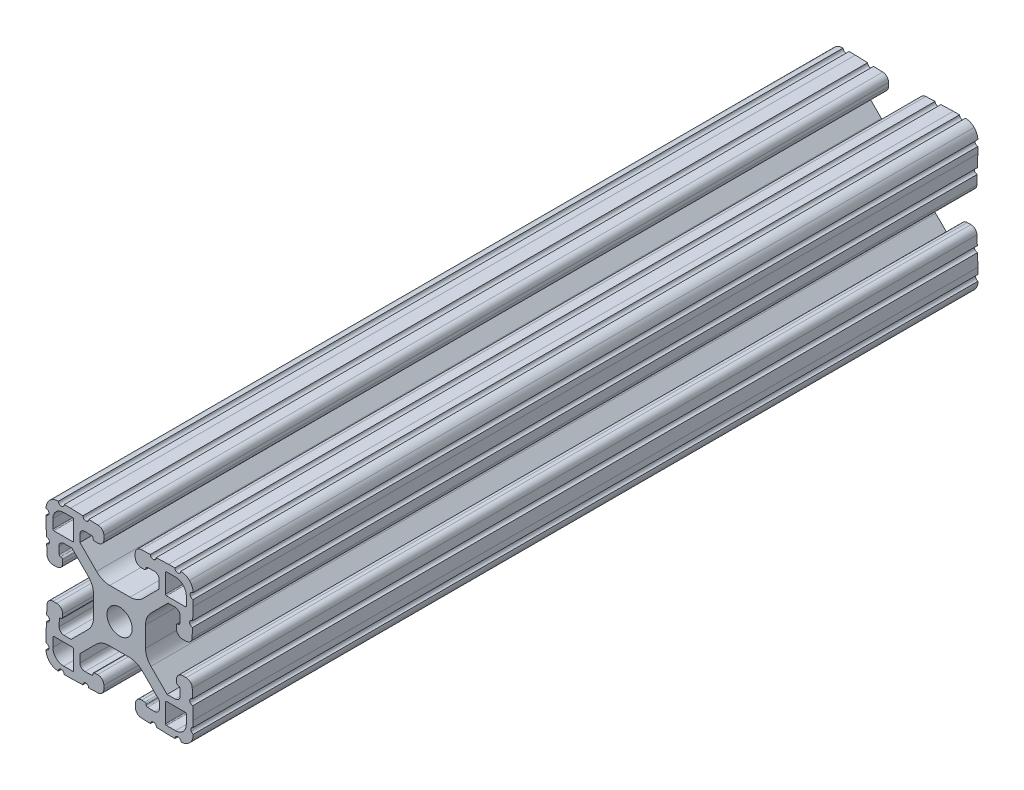
SolidWorks part; units mm, degrees
ref_plane "Front Plane" through (0, 0, 0) normal (0, 0, 1) x (1, 0, 0)
ref_plane "Top Plane" through (0, 0, 0) normal (0, 1, 0) x (1, 0, 0)
ref_plane "Right Plane" through (0, 0, 0) normal (1, 0, 0) x (0, 0, -1)
ref_plane "Plane1" through (0, 0, -25.4) normal (0, 0, -1) x (-1, 0, 0)
sketch "Sketch1" plane through (0, 0, -25.4) normal (0, 0, -1) x (-1, 0, 0)
  line L0 (-83.3577, 88.2941) -> (-83.3577, 93.1709)
  line L1 (-83.1037, 93.4249) -> (-80.767, 93.4249)
  line L2 (-77.9729, 90.6309) -> (-77.9729, 88.2941)
  line L3 (-78.2269, 88.0401) -> (-83.1037, 88.0401)
  line L4 (-83.3577, 59.2291) -> (-83.3577, 64.1059)
  line L5 (-83.1037, 64.3599) -> (-78.2269, 64.3599)
  line L6 (-77.9729, 64.1059) -> (-77.9729, 61.7691)
  line L7 (-80.767, 58.9751) -> (-83.1037, 58.9751)
  line L8 (-107.1423, 93.1709) -> (-107.1423, 88.2941)
  line L9 (-107.3963, 88.0401) -> (-112.2731, 88.0401)
  line L10 (-112.5271, 88.2941) -> (-112.5271, 90.6309)
  line L11 (-109.733, 93.4249) -> (-107.3963, 93.4249)
  line L12 (-107.1423, 64.1059) -> (-107.1423, 59.2291)
  line L13 (-107.3963, 58.9751) -> (-109.733, 58.9751)
  line L14 (-112.5271, 61.7691) -> (-112.5271, 64.1059)
  line L15 (-112.2731, 64.3599) -> (-107.3963, 64.3599)
  line L16 (-88.0437, 91.8626) -> (-86.2967, 91.9236)
  line L17 (-84.9824, 90.6544) -> (-84.9824, 88.8002)
  line L18 (-84.9824, 88.8002) -> (-89.3066, 84.476)
  line L19 (-92.7196, 83.0295) -> (-97.9616, 83.0295)
  line L20 (-101.3202, 84.4207) -> (-105.516, 88.6165)
  line L21 (-105.516, 88.6165) -> (-105.516, 90.7313)
  line L22 (-104.2017, 92.0006) -> (-102.4547, 91.9396)
  line L23 (-101.7262, 91.1059) -> (-100.9297, 91.0781)
  line L24 (-99.2999, 92.6519) -> (-99.2999, 93.5668)
  line L25 (-100.8197, 95.1407) -> (-103.2119, 95.2242)
  line L26 (-104.735, 95.2774) -> (-107.9359, 95.3892)
  line L27 (-107.9359, 95.3892) -> (-109.5615, 95.3892)
  line L28 (-114.2859, 90.6648) -> (-114.2859, 89.0392)
  line L29 (-114.2859, 89.0392) -> (-114.1741, 85.8383)
  line L30 (-114.1209, 84.3152) -> (-114.0374, 81.9231)
  line L31 (-112.4635, 80.4032) -> (-111.5486, 80.4032)
  line L32 (-109.9748, 82.033) -> (-110.0026, 82.8295)
  line L33 (-110.8377, 83.5577) -> (-110.8987, 85.3047)
  line L34 (-109.6294, 86.619) -> (-107.8072, 86.619)
  line L35 (-107.8072, 86.619) -> (-103.3649, 82.1768)
  line L36 (-101.9737, 78.8182) -> (-101.9737, 73.576)
  line L37 (-103.3649, 70.2174) -> (-107.5607, 66.0217)
  line L38 (-107.5607, 66.0217) -> (-109.6524, 66.0217)
  line L39 (-110.9217, 67.336) -> (-110.8607, 69.083)
  line L40 (-110.0322, 69.8124) -> (-110.0043, 70.6089)
  line L41 (-111.5782, 72.2387) -> (-112.4931, 72.2387)
  line L42 (-114.0669, 70.7189) -> (-114.1505, 68.3267)
  line L43 (-114.2036, 66.8036) -> (-114.3154, 63.6027)
  line L44 (-114.3154, 63.6027) -> (-114.3154, 61.9626)
  line L45 (-109.6111, 57.1437) -> (-107.9855, 57.1437)
  line L46 (-107.9855, 57.1437) -> (-104.7846, 57.2555)
  line L47 (-103.2615, 57.3086) -> (-100.8694, 57.3922)
  line L48 (-99.3495, 58.966) -> (-99.3495, 59.8809)
  line L49 (-100.9794, 61.4548) -> (-101.7758, 61.4269)
  line L50 (-102.5054, 60.599) -> (-104.2524, 60.538)
  line L51 (-105.5667, 61.8072) -> (-105.5667, 63.6295)
  line L52 (-105.5667, 63.6295) -> (-101.1311, 68.065)
  line L53 (-97.7725, 69.4562) -> (-92.5304, 69.4562)
  line L54 (-89.1717, 68.065) -> (-84.976, 63.8692)
  line L55 (-84.976, 63.8692) -> (-84.976, 61.7811)
  line L56 (-86.2903, 60.5118) -> (-88.0373, 60.5728)
  line L57 (-88.7596, 61.4332) -> (-89.5561, 61.461)
  line L58 (-91.1859, 59.8872) -> (-91.1859, 58.9723)
  line L59 (-89.6661, 57.3985) -> (-87.2739, 57.3149)
  line L60 (-85.7508, 57.2617) -> (-82.5499, 57.15)
  line L61 (-82.5499, 57.15) -> (-80.9244, 57.15)
  line L62 (-76.2, 61.8744) -> (-76.2, 63.4999)
  line L63 (-76.2, 63.4999) -> (-76.3117, 66.7008)
  line L64 (-76.3649, 68.2239) -> (-76.4484, 70.6161)
  line L65 (-78.0223, 72.1359) -> (-78.9372, 72.1359)
  line L66 (-80.511, 70.5061) -> (-80.4832, 69.7096)
  line L67 (-79.6552, 68.9801) -> (-79.5942, 67.2331)
  line L68 (-80.8634, 65.9188) -> (-82.6857, 65.9188)
  line L69 (-82.6857, 65.9188) -> (-87.1213, 70.3543)
  line L70 (-88.5125, 73.7128) -> (-88.5126, 78.955)
  line L71 (-87.1214, 82.3137) -> (-82.9257, 86.5095)
  line L72 (-82.9257, 86.5095) -> (-80.8375, 86.5095)
  line L73 (-79.5682, 85.1951) -> (-79.6293, 83.4482)
  line L74 (-80.4896, 82.7258) -> (-80.5175, 81.9294)
  line L75 (-78.9436, 80.2995) -> (-78.0287, 80.2995)
  line L76 (-76.4549, 81.8194) -> (-76.3713, 84.2115)
  line L77 (-76.3182, 85.7346) -> (-76.2064, 88.9355)
  line L78 (-76.2064, 88.9355) -> (-76.2064, 90.5611)
  line L79 (-80.9308, 95.2855) -> (-82.5564, 95.2855)
  line L80 (-82.5564, 95.2855) -> (-85.7573, 95.1737)
  line L81 (-87.2803, 95.1205) -> (-89.6725, 95.037)
  line L82 (-91.1924, 93.4632) -> (-91.1924, 92.5483)
  line L83 (-89.5625, 90.9744) -> (-88.7661, 91.0023)
  arc A0 (-83.3577, 93.1709) -> (-83.1037, 93.4249) centre (-83.1037, 93.1709) cw
  arc A1 (-80.767, 93.4249) -> (-77.9729, 90.6309) centre (-80.7669, 90.6309) cw
  arc A2 (-77.9729, 88.2941) -> (-78.2269, 88.0401) centre (-78.2269, 88.2941) cw
  arc A3 (-83.1037, 88.0401) -> (-83.3577, 88.2941) centre (-83.1037, 88.2941) cw
  arc A4 (-83.1037, 58.9751) -> (-83.3577, 59.2291) centre (-83.1037, 59.2291) cw
  arc A5 (-83.3577, 64.1059) -> (-83.1037, 64.3599) centre (-83.1037, 64.1059) cw
  arc A6 (-78.2269, 64.3599) -> (-77.9729, 64.1059) centre (-78.2269, 64.1059) cw
  arc A7 (-77.9729, 61.7691) -> (-80.767, 58.9751) centre (-80.7669, 61.7691) cw
  arc A8 (-107.3963, 93.4249) -> (-107.1423, 93.1709) centre (-107.3963, 93.1709) cw
  arc A9 (-107.1423, 88.2941) -> (-107.3963, 88.0401) centre (-107.3963, 88.2941) cw
  arc A10 (-112.2731, 88.0401) -> (-112.5271, 88.2941) centre (-112.2731, 88.2941) cw
  arc A11 (-112.5271, 90.6309) -> (-109.733, 93.4249) centre (-109.7331, 90.6309) cw
  arc A12 (-107.1423, 59.2291) -> (-107.3963, 58.9751) centre (-107.3963, 59.2291) cw
  arc A13 (-109.733, 58.9751) -> (-112.5271, 61.7691) centre (-109.7331, 61.7691) cw
  arc A14 (-112.5271, 64.1059) -> (-112.2731, 64.3599) centre (-112.2731, 64.1059) cw
  arc A15 (-107.3963, 64.3599) -> (-107.1423, 64.1059) centre (-107.3963, 64.1059) cw
  circle A16 centre (-95.25, 76.2) radius 3.2639
  arc A17 (-88.7661, 91.0023) -> (-88.3984, 91.383) centre (-88.7794, 91.383) ccw
  arc A18 (-88.3984, 91.383) -> (-88.0437, 91.8626) centre (-88.0304, 91.4819) cw
  arc A19 (-86.2967, 91.9236) -> (-84.9824, 90.6544) centre (-86.2524, 90.6544) cw
  arc A20 (-89.3066, 84.476) -> (-92.7196, 83.0295) centre (-92.7196, 87.7793) cw
  arc A21 (-97.9616, 83.0295) -> (-101.3202, 84.4207) centre (-97.9616, 87.7793) cw
  arc A22 (-105.516, 90.7313) -> (-104.2017, 92.0006) centre (-104.246, 90.7313) cw
  arc A23 (-102.4547, 91.9396) -> (-102.087, 91.5588) centre (-102.468, 91.5588) cw
  arc A24 (-102.087, 91.5588) -> (-101.7262, 91.1059) centre (-101.7129, 91.4867) ccw
  arc A25 (-100.9297, 91.0781) -> (-99.2999, 92.6519) centre (-100.8747, 92.6519) ccw
  arc A26 (-99.2999, 93.5668) -> (-100.8197, 95.1407) centre (-100.8747, 93.5668) ccw
  arc A27 (-103.2119, 95.2242) -> (-104.735, 95.2774) centre (-103.9735, 95.2508) cw
  arc A28 (-109.5615, 95.3892) -> (-111.0855, 95.3892) centre (-110.3235, 95.3892) cw
  arc A29 (-111.0855, 95.3892) -> (-113.3432, 94.4465) centre (-111.0855, 92.2142) ccw
  arc A30 (-113.3432, 94.4465) -> (-114.2859, 92.1888) centre (-111.1109, 92.1888) ccw
  arc A31 (-114.2859, 92.1888) -> (-114.2859, 90.6648) centre (-114.2859, 91.4268) cw
  arc A32 (-114.1741, 85.8383) -> (-114.1209, 84.3152) centre (-114.1475, 85.0768) cw
  arc A33 (-114.0374, 81.9231) -> (-112.4635, 80.4032) centre (-112.4635, 81.978) ccw
  arc A34 (-111.5486, 80.4032) -> (-109.9748, 82.033) centre (-111.5486, 81.978) ccw
  arc A35 (-110.0026, 82.8295) -> (-110.3834, 83.1972) centre (-110.3834, 82.8162) ccw
  arc A36 (-110.3834, 83.1972) -> (-110.8377, 83.5577) centre (-110.4569, 83.571) cw
  arc A37 (-110.8987, 85.3047) -> (-109.6294, 86.619) centre (-109.6294, 85.349) cw
  arc A38 (-103.3649, 82.1768) -> (-101.9737, 78.8182) centre (-106.7235, 78.8182) cw
  arc A39 (-101.9737, 73.576) -> (-103.3649, 70.2174) centre (-106.7235, 73.576) cw
  arc A40 (-109.6524, 66.0217) -> (-110.9217, 67.336) centre (-109.6524, 67.2917) cw
  arc A41 (-110.8607, 69.083) -> (-110.4799, 69.4507) centre (-110.4799, 69.0697) cw
  arc A42 (-110.4799, 69.4507) -> (-110.0322, 69.8124) centre (-110.413, 69.8257) ccw
  arc A43 (-110.0043, 70.6089) -> (-111.5782, 72.2387) centre (-111.5782, 70.6639) ccw
  arc A44 (-112.4931, 72.2387) -> (-114.0669, 70.7189) centre (-112.4931, 70.6639) ccw
  arc A45 (-114.1505, 68.3267) -> (-114.2036, 66.8036) centre (-114.1771, 67.5652) cw
  arc A46 (-114.3154, 61.9626) -> (-114.3332, 60.4644) centre (-114.4639, 61.2152) cw
  arc A47 (-114.3332, 60.4644) -> (-113.3928, 58.0864) centre (-111.1605, 60.3441) ccw
  arc A48 (-113.3928, 58.0864) -> (-111.1351, 57.1437) centre (-111.1351, 60.3187) ccw
  arc A49 (-111.1351, 57.1437) -> (-109.6111, 57.1437) centre (-110.3731, 57.1437) cw
  arc A50 (-104.7846, 57.2555) -> (-103.2615, 57.3086) centre (-104.0231, 57.2821) cw
  arc A51 (-100.8694, 57.3922) -> (-99.3495, 58.966) centre (-100.9243, 58.966) ccw
  arc A52 (-99.3495, 59.8809) -> (-100.9794, 61.4548) centre (-100.9243, 59.8809) ccw
  arc A53 (-101.7758, 61.4269) -> (-102.1435, 61.0462) centre (-101.7625, 61.0462) ccw
  arc A54 (-102.1435, 61.0462) -> (-102.5054, 60.599) centre (-102.5187, 60.9797) cw
  arc A55 (-104.2524, 60.538) -> (-105.5667, 61.8072) centre (-104.2967, 61.8072) cw
  arc A56 (-101.1311, 68.065) -> (-97.7725, 69.4562) centre (-97.7725, 64.7064) cw
  arc A57 (-92.5304, 69.4562) -> (-89.1717, 68.065) centre (-92.5304, 64.7064) cw
  arc A58 (-84.976, 61.7811) -> (-86.2903, 60.5118) centre (-86.246, 61.7811) cw
  arc A59 (-88.0373, 60.5728) -> (-88.405, 60.9536) centre (-88.024, 60.9536) cw
  arc A60 (-88.405, 60.9536) -> (-88.7596, 61.4332) centre (-88.7729, 61.0524) ccw
  arc A61 (-89.5561, 61.461) -> (-91.1859, 59.8872) centre (-89.6111, 59.8872) ccw
  arc A62 (-91.1859, 58.9723) -> (-89.6661, 57.3985) centre (-89.6111, 58.9723) ccw
  arc A63 (-87.2739, 57.3149) -> (-85.7508, 57.2617) centre (-86.5124, 57.2883) cw
  arc A64 (-80.9244, 57.15) -> (-79.4004, 57.15) centre (-80.1624, 57.15) cw
  arc A65 (-79.4004, 57.15) -> (-77.1426, 58.0927) centre (-79.4004, 60.325) ccw
  arc A66 (-77.1426, 58.0927) -> (-76.2, 60.3504) centre (-79.375, 60.3504) ccw
  arc A67 (-76.2, 60.3504) -> (-76.2, 61.8744) centre (-76.2, 61.1124) cw
  arc A68 (-76.3117, 66.7008) -> (-76.3649, 68.2239) centre (-76.3383, 67.4624) cw
  arc A69 (-76.4484, 70.6161) -> (-78.0223, 72.1359) centre (-78.0223, 70.5611) ccw
  arc A70 (-78.9372, 72.1359) -> (-80.511, 70.5061) centre (-78.9372, 70.5611) ccw
  arc A71 (-80.4832, 69.7096) -> (-80.1024, 69.342) centre (-80.1024, 69.723) ccw
  arc A72 (-80.1024, 69.342) -> (-79.6552, 68.9801) centre (-80.036, 68.9668) cw
  arc A73 (-79.5942, 67.2331) -> (-80.8634, 65.9188) centre (-80.8634, 67.1888) cw
  arc A74 (-87.1213, 70.3543) -> (-88.5125, 73.7128) centre (-83.7627, 73.7129) cw
  arc A75 (-88.5126, 78.955) -> (-87.1214, 82.3137) centre (-83.7628, 78.9551) cw
  arc A76 (-80.8375, 86.5095) -> (-79.5682, 85.1951) centre (-80.8375, 85.2395) cw
  arc A77 (-79.6293, 83.4482) -> (-80.01, 83.0805) centre (-80.01, 83.4615) cw
  arc A78 (-80.01, 83.0805) -> (-80.4896, 82.7258) centre (-80.1089, 82.7125) ccw
  arc A79 (-80.5175, 81.9294) -> (-78.9436, 80.2995) centre (-78.9436, 81.8743) ccw
  arc A80 (-78.0287, 80.2995) -> (-76.4549, 81.8194) centre (-78.0287, 81.8743) ccw
  arc A81 (-76.3713, 84.2115) -> (-76.3182, 85.7346) centre (-76.3448, 84.9731) cw
  arc A82 (-76.2064, 90.5611) -> (-76.2064, 92.0851) centre (-76.2064, 91.3231) cw
  arc A83 (-76.2064, 92.0851) -> (-77.1491, 94.3428) centre (-79.3814, 92.0851) ccw
  arc A84 (-77.1491, 94.3428) -> (-79.4068, 95.2855) centre (-79.4068, 92.1105) ccw
  arc A85 (-79.4068, 95.2855) -> (-80.9308, 95.2855) centre (-80.1688, 95.2855) cw
  arc A86 (-85.7573, 95.1737) -> (-87.2803, 95.1205) centre (-86.5188, 95.1471) cw
  arc A87 (-89.6725, 95.037) -> (-91.1924, 93.4632) centre (-89.6176, 93.4632) ccw
  arc A88 (-91.1924, 92.5483) -> (-89.5625, 90.9744) centre (-89.6176, 92.5483) ccw
extrude "Boss-Extrude1" add sketch "Sketch1" against normal blind 203.2
